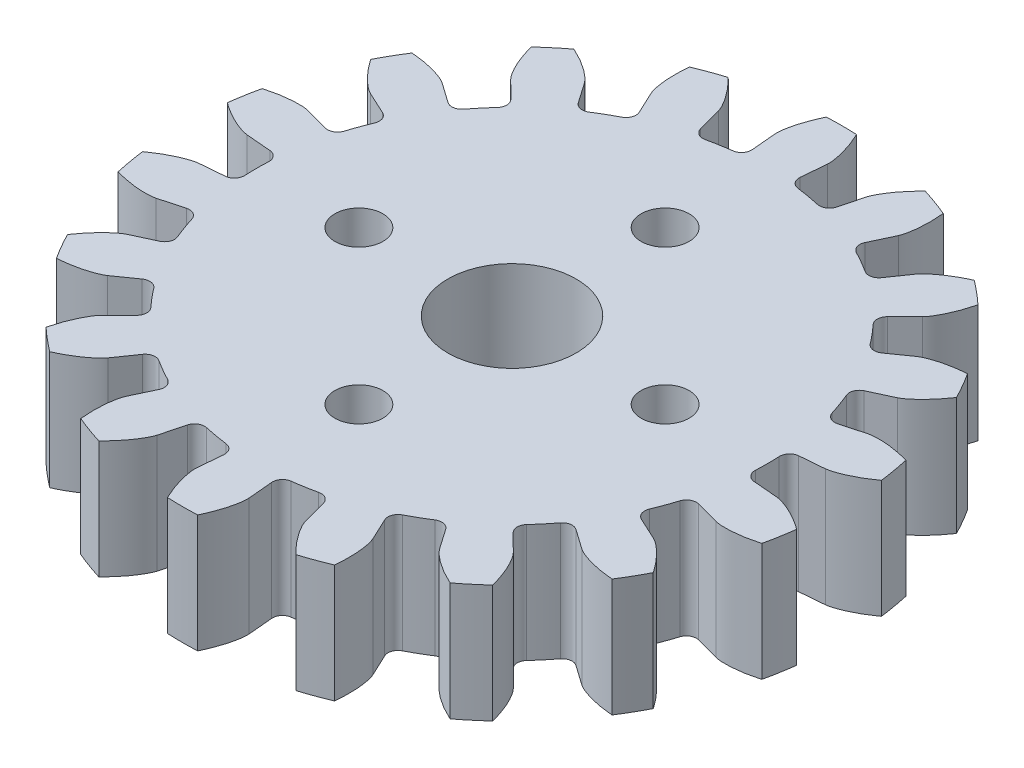
SolidWorks part; units mm, degrees
material "PMMA"
ref_plane "Plan de face" through (0, 0, 0) normal (0, 0, 1) x (1, 0, 0)
ref_plane "Plan de dessus" through (0, 0, 0) normal (0, 1, 0) x (1, 0, 0)
ref_plane "Plan de droite" through (0, 0, 0) normal (1, 0, 0) x (0, 0, -1)
sketch "Esquisse1" plane through (0, 0, 0) normal (0, 1, 0) x (1, 0, 0)
  circle A0 centre (0, 0) radius 14
  dimension "D1" = 28.0001
extrude "Boss.-Extru.1" add sketch "Esquisse1" along normal blind 5
sketch "Esquisse2" plane through (0, 5, 0) normal (0, 1, 0) x (1, 0, 0)
  line L0 (0, 0) -> (12.2811, 1.0359) construction
  line L1 (0, 0) -> (12.2811, -1.0359) construction
  line L2 (12.2811, 1.0359) -> (10.8116, 0.9119)
  line L3 (12.2811, -1.0359) -> (10.8116, -0.9119)
  circle A0 centre (0, 0) radius 14 construction
  circle A1 centre (0, 0) radius 12.6 construction
  circle A2 centre (0, 0) radius 12.3247 construction
  circle A3 centre (0, 0) radius 10.85 construction
  arc A4 (13.8842, 1.7976) -> (13.8842, -1.7976) centre (0, 0) cw
  arc A5 (12.2811, 1.0359) -> (12.2811, -1.0359) centre (0, 0) cw construction
  arc A6 (10.8116, 0.9119) -> (10.8116, -0.9119) centre (0, 0) cw
  spline S0 degree 4 poles (12.2811, 1.0359) (12.2837, 1.0361) (12.2911, 1.0369) (12.305, 1.0388) (12.3277, 1.0424) (12.3564, 1.0478) (12.3935, 1.0555) (12.4371, 1.0658) (12.4848, 1.0783) (12.5365, 1.0932) (12.588, 1.1092) (12.6391, 1.1261) (12.6899, 1.144) (12.7512, 1.1667) (12.8245, 1.1955) (12.9097, 1.2314) (13.0058, 1.2748) (13.1033, 1.3218) (13.1986, 1.3704) (13.2944, 1.4222) (13.3866, 1.4742) (13.4818, 1.5309) (13.5693, 1.5846) (13.6667, 1.6478) (13.745, 1.6996) (13.8475, 1.7712) (13.9078, 1.8144) (13.9781, 1.8661) (14.0092, 1.8896) (14.0283, 1.9041) knots 0 0 0 0 0 0.005377 0.015084 0.028532 0.04661 0.064855 0.092111 0.119476 0.146842 0.174209 0.201575 0.228941 0.256307 0.307035 0.361767 0.4165 0.471232 0.525964 0.580697 0.635429 0.690161 0.744894 0.799626 0.854358 0.909091 0.954545 1 1 1 1 1 construction
  spline S1 degree 4 poles (12.2811, 1.0359) (12.2837, 1.0361) (12.2911, 1.0369) (12.305, 1.0388) (12.3277, 1.0424) (12.3564, 1.0478) (12.3935, 1.0555) (12.4371, 1.0658) (12.4848, 1.0783) (12.5365, 1.0932) (12.588, 1.1092) (12.6391, 1.1261) (12.6899, 1.144) (12.7512, 1.1667) (12.8245, 1.1955) (12.9097, 1.2314) (13.0058, 1.2748) (13.1033, 1.3218) (13.1986, 1.3704) (13.2944, 1.4222) (13.3866, 1.4742) (13.4818, 1.5309) (13.5693, 1.5846) (13.6667, 1.6478) (13.745, 1.6996) (13.8253, 1.7557) (13.8643, 1.7833) (13.8842, 1.7976) knots 0 0 0 0 0 0.005377 0.015084 0.028532 0.04661 0.064855 0.092111 0.119476 0.146842 0.174209 0.201575 0.228941 0.256307 0.307035 0.361767 0.4165 0.471232 0.525964 0.580697 0.635429 0.690161 0.744894 0.799626 0.854358 0.909091 0.909091 0.909091 0.909091 0.909091
  spline S2 degree 4 poles (12.2811, -1.0359) (12.2837, -1.0361) (12.2911, -1.0369) (12.305, -1.0388) (12.3277, -1.0424) (12.3564, -1.0478) (12.3935, -1.0555) (12.4371, -1.0658) (12.4848, -1.0783) (12.5365, -1.0932) (12.588, -1.1092) (12.6391, -1.1261) (12.6899, -1.144) (12.7512, -1.1667) (12.8245, -1.1955) (12.9097, -1.2314) (13.0058, -1.2748) (13.1033, -1.3218) (13.1986, -1.3704) (13.2944, -1.4222) (13.3866, -1.4742) (13.4818, -1.5309) (13.5693, -1.5846) (13.6667, -1.6478) (13.745, -1.6996) (13.8475, -1.7712) (13.9078, -1.8144) (13.9781, -1.8661) (14.0092, -1.8896) (14.0283, -1.9041) knots 0 0 0 0 0 0.005377 0.015084 0.028532 0.04661 0.064855 0.092111 0.119476 0.146842 0.174209 0.201575 0.228941 0.256307 0.307035 0.361767 0.4165 0.471232 0.525964 0.580697 0.635429 0.690161 0.744894 0.799626 0.854358 0.909091 0.954545 1 1 1 1 1 construction
  spline S3 degree 4 poles (12.2811, -1.0359) (12.2837, -1.0361) (12.2911, -1.0369) (12.305, -1.0388) (12.3277, -1.0424) (12.3564, -1.0478) (12.3935, -1.0555) (12.4371, -1.0658) (12.4848, -1.0783) (12.5365, -1.0932) (12.588, -1.1092) (12.6391, -1.1261) (12.6899, -1.144) (12.7512, -1.1667) (12.8245, -1.1955) (12.9097, -1.2314) (13.0058, -1.2748) (13.1033, -1.3218) (13.1986, -1.3704) (13.2944, -1.4222) (13.3866, -1.4742) (13.4818, -1.5309) (13.5693, -1.5846) (13.6667, -1.6478) (13.745, -1.6996) (13.8253, -1.7557) (13.8643, -1.7833) (13.8842, -1.7976) knots 0 0 0 0 0 0.005377 0.015084 0.028532 0.04661 0.064855 0.092111 0.119476 0.146842 0.174209 0.201575 0.228941 0.256307 0.307035 0.361767 0.4165 0.471232 0.525964 0.580697 0.635429 0.690161 0.744894 0.799626 0.854358 0.909091 0.909091 0.909091 0.909091 0.909091
  dimension "D1" = 28.0001
  dimension "D2" = 25.2001
  dimension "D3" = 24.6494
  dimension "D4" = 21.7001
extrude "Enlèv. mat.-Extru.3" cut sketch "Esquisse2" against normal through all
fillet "Congé1" radius 0.4228 2 edges at (10.8116, 2.5, 0.9119) (10.8116, 2.5, -0.9119)
pattern_circular "Répétition circulaire2" count 18 over 360 about axis through (0, 5, 0) along (0, -1, 0) of "Enlèv. mat.-Extru.3", "Congé1"
sketch "Esquisse3" plane through (0, 5, 0) normal (0, 1, 0) x (1, 0, 0)
  circle A0 centre (0, 0) radius 2.725
  dimension "D1" = 5.45
extrude "Enlèv. mat.-Extru.4" cut sketch "Esquisse3" against normal through all
sketch "Esquisse4" plane through (0, 5, 0) normal (0, 1, 0) x (1, 0, 0)
  line L0 (0, 0) -> (6.5, 0) construction
  circle A0 centre (6.5, 0) radius 1.02
  dimension "D1" = 2.04
  dimension "D2" = 6.5
extrude "Enlèv. mat.-Extru.5" cut sketch "Esquisse4" against normal through all
pattern_circular "Répétition circulaire3" count 4 over 360 about axis through (0, 0, 0) along (0, 1, 0) of "Enlèv. mat.-Extru.5"
equation "\"DiametralPitch\"= 18.1428/25.4"
equation "\"NumTeeth\"= 18"
equation "\"PressureAngle\"= 12"
equation "\"Addendum\"= 1 / \"DiametralPitch\""
equation "\"Dedendum\"= 1.25 / \"DiametralPitch\""
equation "\"WorkingDepth\"= 2 / \"DiametralPitch\""
equation "\"WholeDepth\"= 2.25 / \"DiametralPitch\""
equation "\"Clearance\"= 0.25 / \"DiametralPitch\""
equation "\"ToothThickness\"= 1.5708 / \"DiametralPitch\""
equation "\"CircularPitch\"= pi / \"DiametralPitch\""
equation "\"PitchCircle\"= \"NumTeeth\" / \"DiametralPitch\""
equation "\"OutsideDiameter\"= ( \"NumTeeth\" + 2 ) / \"DiametralPitch\""
equation "\"Fillet\"= \"Clearance\" * cos ( \"PressureAngle\" ) * tan ( ( 90 + \"PressureAngle\" ) / 2 )"
equation "\"AddendumCircle\"= \"PitchCircle\" + ( 2 * \"Addendum\" )"
equation "\"DedendumCircle\"= \"PitchCircle\" - ( 2 * \"Dedendum\" )"
equation "\"BaseCircle\"= \"PitchCircle\" * cos ( \"PressureAngle\" )"
equation "\"PitchAngle\"= 360deg / \"NumTeeth\""
equation "\"Alpha\"= sqr ( \"PitchCircle\" ^ 2 - \"BaseCircle\" ^ 2 ) / \"BaseCircle\" * 180 / PI - \"PressureAngle\""
equation "\"Beta\"= ( \"PitchAngle\" / 4 - \"Alpha\" )"
equation "\"Phi\"= sqr ( ( \"AddendumCircle\" / 2 ) ^ 2 - ( \"BaseCircle\" / 2 ) ^ 2 ) / ( \"BaseCircle\" / 2 )"
equation "\"D1@Esquisse1\"=\"OutsideDiameter\""
equation "\"D1@Esquisse2\"=\"OutsideDiameter\""
equation "\"D2@Esquisse2\"=\"PitchCircle\""
equation "\"D3@Esquisse2\"=\"BaseCircle\""
equation "\"D4@Esquisse2\"=\"DedendumCircle\""
equation "\"D1@Congé1\"=\"Fillet\""
equation "\"D1@Répétition circulaire2\"=\"NumTeeth\""
